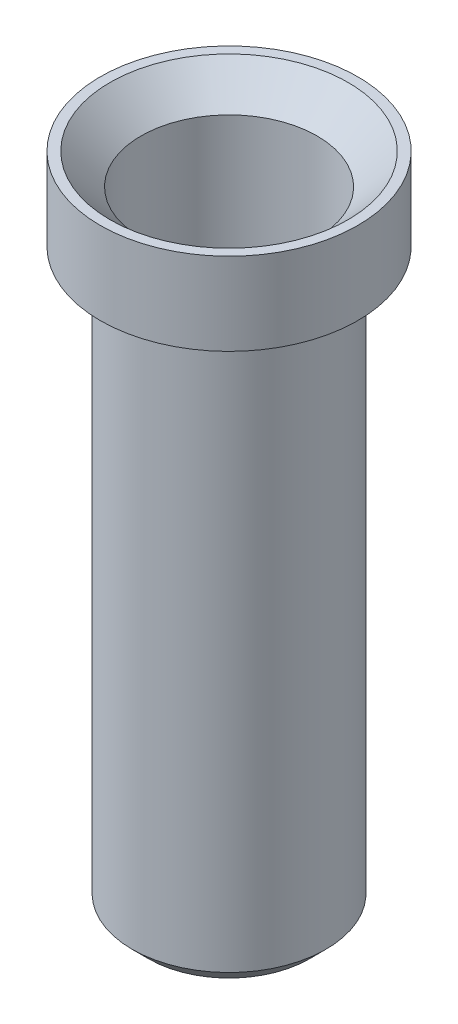
SolidWorks part; units mm, degrees
ref_plane "前视基准面" through (0, 0, 0) normal (0, 0, 1) x (1, 0, 0)
ref_plane "上视基准面" through (0, 0, 0) normal (0, 1, 0) x (1, 0, 0)
ref_plane "右视基准面" through (0, 0, 0) normal (1, 0, 0) x (0, 0, -1)
sketch "草图1" plane through (0, 0, 0) normal (0, 0, 1) x (1, 0, 0)
  line L0 (0, 8.2388) -> (0, -6.3059) construction
  line L1 (0, -5.6) -> (-0.94, -5.6)
  line L2 (-0.94, -5.6) -> (-0.94, 0)
  line L3 (-0.94, 0) -> (-1.25, 0)
  line L4 (-1.25, 0) -> (-1.25, 0.8)
  line L5 (-1.25, 0.8) -> (-1.155, 0.8)
  line L6 (-1.155, 0.8) -> (-0.855, 0.5)
  line L10 (-0.855, 0.5) -> (-0.855, -4.4)
  line L11 (-0.855, -4.4) -> (0, -4.9703)
  line L12 (5.0295, 0) -> (-9.301, 0) construction
  line L13 (0, -5.6) -> (0, -4.9703)
  point P5 (0, -4.9703)
  point P15 (-0.47, -5.6)
  point P23 (-1.25, 0.4)
  dimension "D1" = 5.6
  dimension "D2" = 0.8
  dimension "D3" = 0.855
  dimension "D4" = 1.155
  dimension "D5" = 0.94
  dimension "D6" = 1.25
  dimension "D7" = 5.2
  dimension "D8" = 0.3
revolve "旋转1" add sketch "草图1" angle 360 about L0
chamfer "倒角1" distance 0.16 angle 45 1 edges at (0, -5.6, 0.94)
